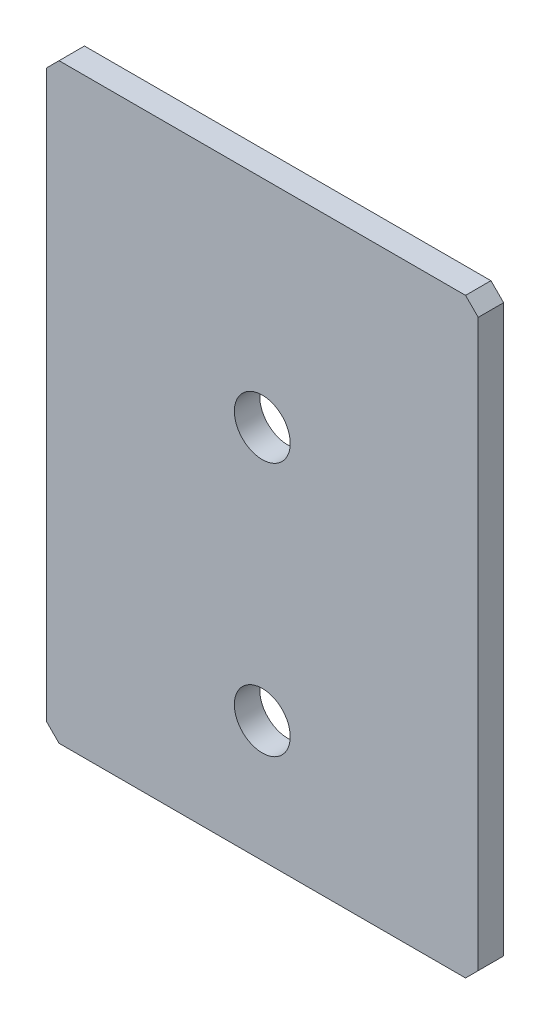
SolidWorks part; units mm, degrees
ref_plane "Ön Düzlem" through (0, 0, 0) normal (0, 0, 1) x (1, 0, 0)
ref_plane "Üst Düzlem" through (0, 0, 0) normal (0, 1, 0) x (1, 0, 0)
ref_plane "Sağ Düzlem" through (0, 0, 0) normal (1, 0, 0) x (0, 0, -1)
sketch "Sketch1" plane through (0, 0, 0) normal (0, 0, 1) x (1, 0, 0)
  line L0 (0, 0) -> (0, -100) construction
  line L6 (-85, 85) -> (85, 85)
  line L7 (-85, 85) -> (-85, -147.7179)
  line L8 (-85, -147.7179) -> (85, -147.7179)
  line L9 (85, 85) -> (85, -147.7179)
  circle A0 centre (0, 0) radius 11
  circle A1 centre (0, -100) radius 11
  circle A2 centre (0, 0) radius 85 construction
  point P6 (99.2097, -190.609)
  point P11 (0, -147.7179)
  dimension "D1" = 22
  dimension "D2" = 100
  dimension "D3" = 170
extrude "Boss-Extrude1" add sketch "Sketch1" along normal blind 10
chamfer "Chamfer1" distance 5 angle 45 4 edges at (85, -147.7179, 5) (-85, -147.7179, 5) (-85, 85, 5) (85, 85, 5)
